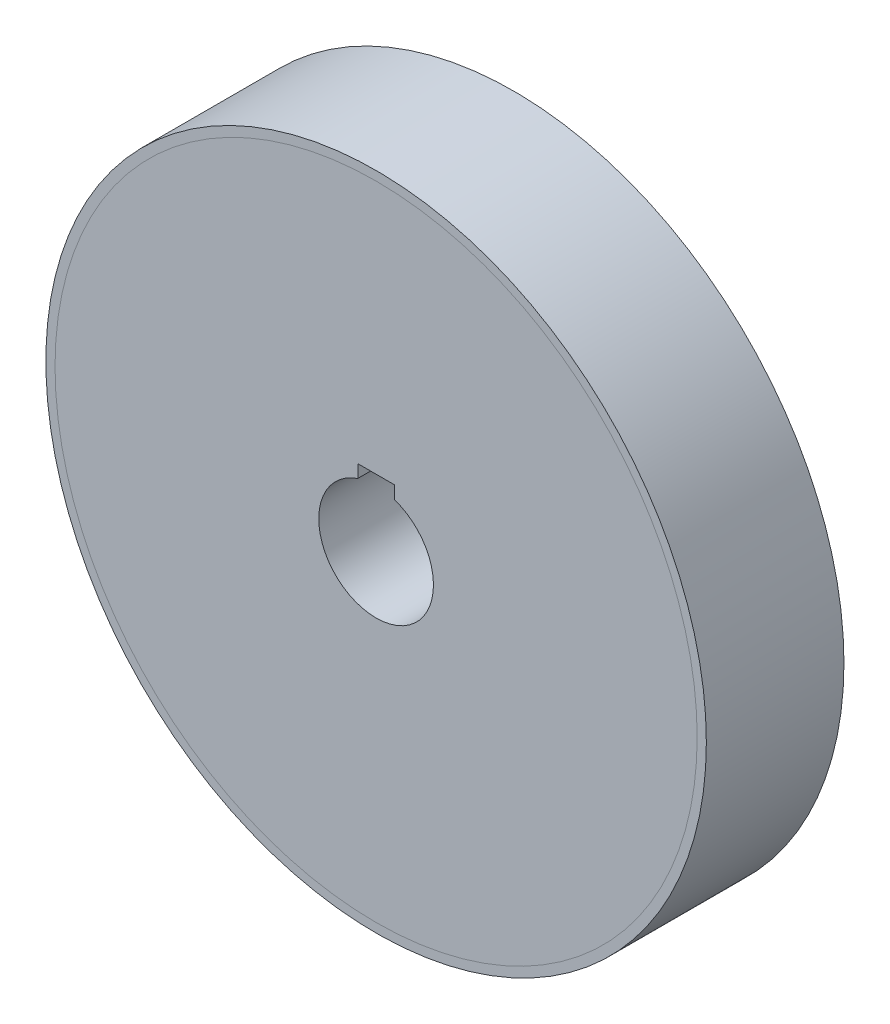
SolidWorks part; units mm, degrees
material "1.7225 (42CrMo4)"
ref_plane "Front Plane" through (0, 0, 0) normal (0, 0, 1) x (1, 0, 0)
ref_plane "Top Plane" through (0, 0, 0) normal (0, 1, 0) x (1, 0, 0)
ref_plane "Right Plane" through (0, 0, 0) normal (1, 0, 0) x (0, 0, -1)
sketch "Sketch1" plane through (0, 0, 0) normal (0, 0, 1) x (1, 0, 0)
  circle A0 centre (0, 0) radius 140
  dimension "D1" = 280
extrude "Boss-Extrude1" add sketch "Sketch1" along normal blind 60
sketch "Sketch2" plane through (0, 0, 60) normal (0, 0, 1) x (1, 0, 0)
  circle A0 centre (0, 0) radius 25
  dimension "D1" = 50
extrude "Cut-Extrude2" cut sketch "Sketch2" against normal through all
sketch "Sketch3" plane through (0, 0, 60) normal (0, 0, 1) x (1, 0, 0)
  line L0 (0, 0) -> (0, 140) construction
  line L1 (-8, 23.6854) -> (-8, 29.3)
  line L2 (-8, 29.3) -> (8, 29.3)
  line L3 (8, 23.6854) -> (8, 29.3)
  circle A0 centre (0, 0) radius 140 construction
  circle A1 centre (0, 0) radius 25 construction
  arc A2 (8, 23.6854) -> (-8, 23.6854) centre (0, 0) ccw
  point P13 (0, 29.3)
  dimension "D1" = 16
  dimension "D2" = 4.3
extrude "Cut-Extrude3" cut sketch "Sketch3" against normal through all
sketch "Sketch4" plane through (0, 0, 60) normal (0, 0, 1) x (1, 0, 0)
  circle A0 centre (0, 0) radius 144
  circle A1 centre (0, 0) radius 140 construction
  circle A2 centre (0, 0) radius 140
  dimension "D1" = 288
extrude "Boss-Extrude2" add sketch "Sketch4" against normal up to surface (60 mm away) separate body up to face at (0, 14.3214, 0)
